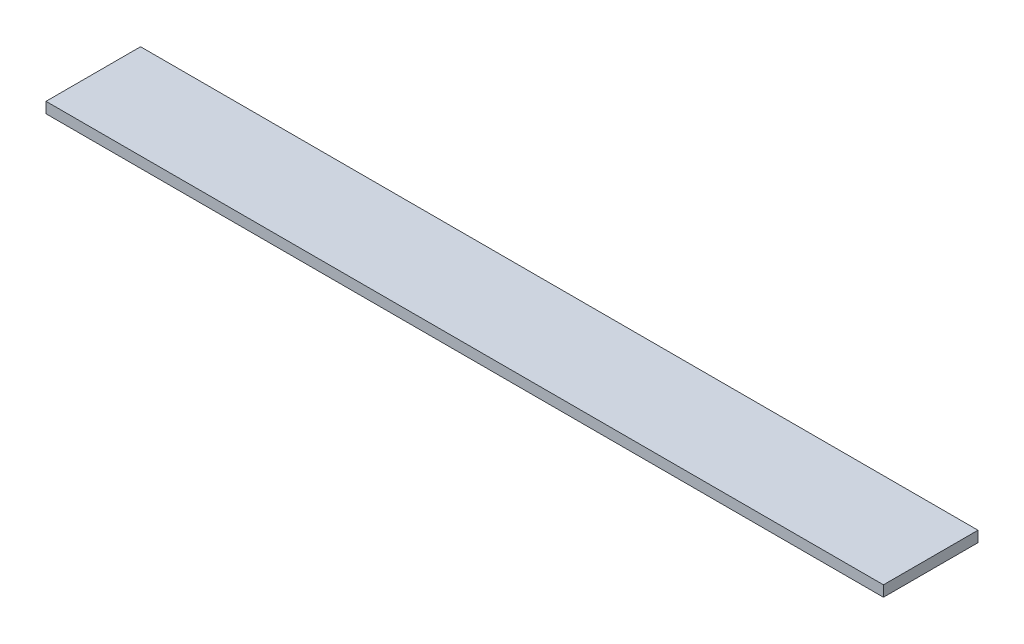
SolidWorks part; units mm, degrees
ref_plane "Alzado" through (0, 0, 0) normal (0, 0, 1) x (1, 0, 0)
ref_plane "Planta" through (0, 0, 0) normal (0, 1, 0) x (1, 0, 0)
ref_plane "Vista lateral" through (0, 0, 0) normal (1, 0, 0) x (0, 0, -1)
sketch "Croquis1" plane through (0, 0, 0) normal (0, 1, 0) x (1, 0, 0)
  line L1 (-155, 17.5) -> (155, 17.5)
  line L2 (-155, 17.5) -> (-155, -17.5)
  line L3 (-155, -17.5) -> (155, -17.5)
  line L4 (155, 17.5) -> (155, -17.5)
  line L5 (-155, 17.5) -> (155, -17.5) construction
  line L6 (-155, -17.5) -> (155, 17.5) construction
  point P0 (0, 0)
  dimension "D1" = 35
  dimension "D2" = 310
extrude "Saliente-Extruir1" add sketch "Croquis1" along normal blind 4
equation "\"venesta\"= 4'grosor de la venesta"
equation "\"policarbonato\"= 4'grosor del policarbonato"
equation "\"carton_trupan\"= 3'grosor del carton trupan caso laser"
equation "\"ancho_tot\"= 310'ancho tot sin llantas"
equation "\"largo_tot\"= 400'largo tot sin camera"
equation "\"alto_estimado\"= 300'alto estimado sin lidar"
equation "\"altoparaqpaselabotella\"= 75'alto estimado para que encaje la botella"
equation "\"alturaruedaloca\"= 22"
equation "\"anchoruedaloca\"= 35"
equation "\"anchopiso1motorybaterias\"= 150"
equation "\"dist-pisorampa\"= 5"
equation "\"anchoultimopiso\"= 170"
equation "\"paredtrasera\"= 100"
equation "\"agarradorcanasta\"= 275'recolector"
equation "\"alturapiso1y2\"= 80"
equation "\"alturapiso2y3\"= 80"
equation "\"D1@Croquis1\"=\"anchoruedaloca\""
equation "\"D2@Croquis1\"=\"ancho_tot\""
equation "\"D1@Saliente-Extruir1\"=\"venesta\""
